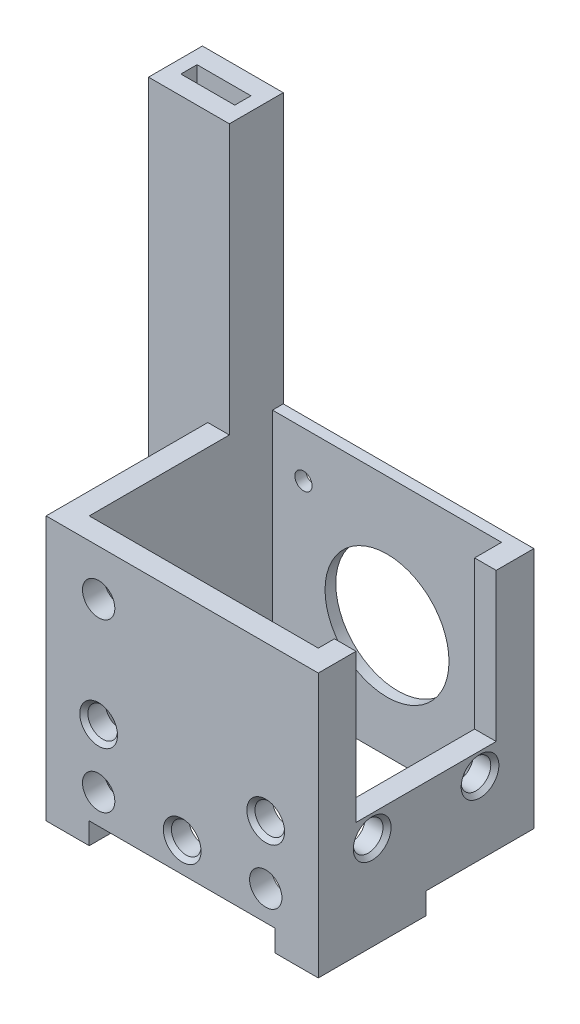
SolidWorks part; units mm, degrees
material "PET"
ref_plane "Front Plane" through (0, 0, 0) normal (0, 0, 1) x (1, 0, 0)
ref_plane "Top Plane" through (0, 0, 0) normal (0, 1, 0) x (1, 0, 0)
ref_plane "Right Plane" through (0, 0, 0) normal (1, 0, 0) x (0, 0, -1)
sketch "Sketch2" plane through (0, 0, 0) normal (0, 1, 0) x (1, 0, 0)
  line L1 (21.25, 17) -> (-21.25, 17)
  line L2 (21.25, 17) -> (21.25, -17)
  line L3 (21.25, -17) -> (-21.25, -17)
  line L4 (-21.25, 17) -> (-21.25, -17)
  line L5 (21.25, 17) -> (-21.25, -17) construction
  line L6 (21.25, -17) -> (-21.25, 17) construction
  line L7 (-25.25, 19) -> (25.25, 19)
  line L8 (-25.25, 19) -> (-25.25, -21)
  line L9 (-25.25, -21) -> (25.25, -21)
  line L10 (25.25, 19) -> (25.25, -21)
  point P1 (0, 0)
  dimension "D1" = 42.5
  dimension "D2" = 34
  dimension "D3" = 4
  dimension "D4" = 4
  dimension "D5" = 4
  dimension "D6" = 2
extrude "Boss-Extrude1" add sketch "Sketch2" along normal blind 45
sketch "Sketch3" plane through (25.25, 0, 0) normal (1, 0, 0) x (0, 0, -1)
  line L0 (-21, 45) -> (19, 45) construction
  line L1 (-14, 45) -> (12, 45)
  line L2 (-14, 45) -> (-14, 17.5)
  line L3 (-14, 17.5) -> (12, 17.5)
  line L4 (12, 45) -> (12, 17.5)
  line L5 (19, 45) -> (19, 0) construction
  line L6 (-21, 45) -> (-21, 0) construction
  line L7 (-21, 0) -> (19, 0) construction
  dimension "D1" = 7
  dimension "D2" = 7
  dimension "D3" = 17.5
extrude "Cut-Extrude1" cut sketch "Sketch3" against normal up to next
sketch "Sketch4" plane through (0, 0, -19) normal (0, 0, -1) x (-1, 0, 0)
  line L0 (-25.25, 0) -> (25.25, 0) construction
  line L1 (0, 0) -> (0, 21) construction
  line L3 (15.5, 36.5) -> (-15.5, 36.5) construction
  line L4 (15.5, 36.5) -> (15.5, 5.5) construction
  line L5 (15.5, 5.5) -> (-15.5, 5.5) construction
  line L6 (-15.5, 36.5) -> (-15.5, 5.5) construction
  line L7 (15.5, 36.5) -> (-15.5, 5.5) construction
  line L8 (15.5, 5.5) -> (-15.5, 36.5) construction
  circle A0 centre (0, 21) radius 11.5
  circle A1 centre (-15.5, 5.5) radius 1.6
  circle A2 centre (15.5, 5.5) radius 1.6
  circle A3 centre (15.5, 36.5) radius 1.6
  dimension "D1" = 21
  dimension "D2" = 23
  dimension "D5" = 3.2
  dimension "D6" = 3.2
  dimension "D7" = 3.2
  dimension "D3" = 31
  dimension "D4" = 31
extrude "Cut-Extrude2" cut sketch "Sketch4" against normal up to next
sketch "Sketch5" plane through (0, 0, 21) normal (0, 0, 1) x (1, 0, 0)
  circle A0 centre (-15.5, 36.5) radius 3
  circle A1 centre (-15.5, 5.5) radius 3
  circle A2 centre (15.5, 5.5) radius 3
  dimension "D1" = 6
  dimension "D2" = 6
  dimension "D3" = 6
extrude "Cut-Extrude3" cut sketch "Sketch5" against normal up to next
sketch "Sketch6" plane through (0, 0, 21) normal (0, 0, 1) x (1, 0, 0)
  line L0 (-15.5, 5.5) -> (-15.5, 27.2301) construction
  line L1 (15.5, 5.5) -> (15.5, 27.2301) construction
  circle A0 centre (-15.5, 16.3651) radius 2.75
  circle A1 centre (0, 5.5) radius 2.75
  circle A2 centre (15.5, 16.3651) radius 2.75
  dimension "D1" = 5.5
  dimension "D2" = 5.5
  dimension "D3" = 5.5
extrude "Cut-Extrude4" cut sketch "Sketch6" against normal up to next
sketch "Sketch7" plane through (25.25, 0, 0) normal (1, 0, 0) x (0, 0, -1)
  line L0 (-11, 13.4406) -> (9, 13.4406) construction
  line L1 (-21, 45) -> (-21, 0) construction
  line L2 (-14, 17.5) -> (12, 17.5) construction
  circle A0 centre (-11, 13.4406) radius 2.75
  circle A1 centre (9, 13.4406) radius 2.75
  dimension "D1" = 5.5
  dimension "D2" = 5.5
  dimension "D3" = 10
  dimension "D4" = 4.0594
  dimension "D5" = 20
extrude "Cut-Extrude5" cut sketch "Sketch7" against normal through all
sketch "Sketch8" plane through (0, 0, 0) normal (0, -1, 0) x (1, 0, 0)
  line L0 (19, 1) -> (17.25, 11)
  line L1 (-25.25, 21) -> (-17.25, 21)
  line L2 (-25.25, 21) -> (-25.25, -4)
  line L3 (-25.25, -4) -> (-17.25, -4)
  line L4 (-17.25, 21) -> (-17.25, -4)
  line L5 (25.25, 21) -> (17.25, 21)
  line L6 (25.25, 21) -> (25.25, 1)
  line L7 (25.25, 1) -> (19, 1)
  line L8 (17.25, 21) -> (17.25, 11)
  dimension "D1" = 20
  dimension "D2" = 8
  dimension "D3" = 8
  dimension "D4" = 25
  dimension "D5" = 1.75
  dimension "D6" = 10
extrude "Boss-Extrude2" add sketch "Sketch8" along normal blind 4
sketch "Sketch9" plane through (0, -4, 0) normal (0, -1, 0) x (1, 0, 0)
  line L0 (-21.25, 21) -> (-21.25, -4) construction
  line L1 (-17.25, 21) -> (-25.25, 21) construction
  line L2 (-25.25, -4) -> (-17.25, -4) construction
  line L3 (21.25, 21) -> (21.25, 1) construction
  line L4 (25.25, 21) -> (17.25, 21) construction
  line L5 (19, 1) -> (25.25, 1) construction
  circle A0 centre (-21.25, 13) radius 2.25
  circle A1 centre (-21.25, 0.5) radius 2.25
  circle A2 centre (21.25, 6) radius 2.25
  circle A3 centre (21.25, 16) radius 2.25
  dimension "D1" = 4.5
  dimension "D2" = 4.5
  dimension "D3" = 4.5
  dimension "D4" = 8
  dimension "D5" = 5
  dimension "D6" = 5
  dimension "D7" = 4.5
  dimension "D8" = 4.5
extrude "Cut-Extrude6" cut sketch "Sketch9" against normal up to surface (4 mm away) up to face at (-19.25, 0, 6.5)
chamfer "Chamfer1" distance 0.75 angle 45 11 edges at (18.25, 16.3651, 21) (2.75, 5.5, 21) (-12.75, 16.3651, 21) (-25.25, 13.4406, -11.75) (-25.25, 13.4406, 8.25) (-21.25, -4, 10.75) (21.25, -4, 13.75) (21.25, -4, 3.75) (-21.25, -4, -1.75) (25.25, 13.4406, -11.75) (25.25, 13.4406, 8.25)
sketch "Sketch10" plane through (0, 45, 0) normal (0, 1, 0) x (1, 0, 0)
  line L0 (25.25, 19) -> (-25.25, 19) construction
  line L1 (-21.25, 19) -> (-36.25, 19)
  line L2 (-21.25, 19) -> (-21.25, 9)
  line L3 (-21.25, 9) -> (-36.25, 9)
  line L4 (-36.25, 19) -> (-36.25, 9)
  line L5 (-21.25, 17) -> (-21.25, -17) construction
  dimension "D1" = 15
  dimension "D2" = 10
extrude "Boss-Extrude3" add sketch "Sketch10" against normal blind 25 and the other way blind 50
sketch "Sketch11" plane through (0, 95, 0) normal (0, 1, 0) x (1, 0, 0)
  line L0 (-36.25, 9) -> (-21.25, 19) construction
  line L2 (-23.75, 15.5) -> (-33.75, 15.5)
  line L3 (-23.75, 15.5) -> (-23.75, 12.5)
  line L4 (-23.75, 12.5) -> (-33.75, 12.5)
  line L5 (-33.75, 15.5) -> (-33.75, 12.5)
  line L6 (-23.75, 15.5) -> (-33.75, 12.5) construction
  line L7 (-23.75, 12.5) -> (-33.75, 15.5) construction
  point P4 (-28.75, 14)
  dimension "D1" = 3
  dimension "D2" = 10
extrude "Cut-Extrude7" cut sketch "Sketch11" against normal up to surface (75 mm away) up to face at (-30.75, 20, -14)
